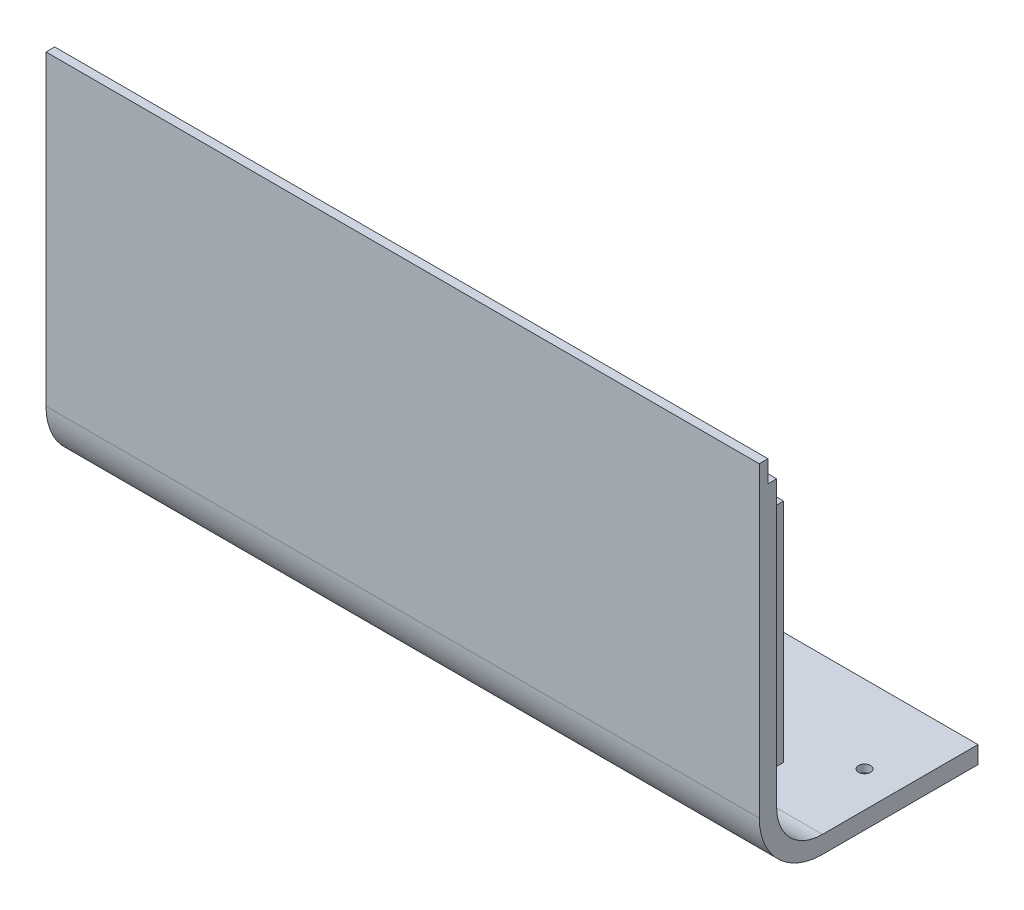
SolidWorks part; units mm, degrees
ref_plane "Alzado" through (0, 0, 0) normal (0, 0, 1) x (1, 0, 0)
ref_plane "Planta" through (0, 0, 0) normal (0, 1, 0) x (1, 0, 0)
ref_plane "Vista lateral" through (0, 0, 0) normal (1, 0, 0) x (0, 0, -1)
sketch "Croquis2" plane through (0, 0, 0) normal (1, 0, 0) x (0, 0, -1)
  line L0 (37, 0) -> (37, -3.2)
  line L1 (8.4, 0) -> (37, 0)
  line L2 (0, 8.4) -> (0, 239.6)
  line L3 (8.4, 248) -> (37, 248)
  line L5 (37, 248) -> (37, 251.2)
  line L6 (37, -3.2) -> (8.4, -3.2)
  line L7 (37, 251.2) -> (8.4, 251.2)
  line L8 (-3.2, 239.6) -> (-3.2, 8.4)
  arc A0 (8.4, 248) -> (0, 239.6) centre (8.4, 239.6) ccw
  arc A1 (0, 8.4) -> (8.4, 0) centre (8.4, 8.4) ccw
  arc A4 (8.4, 251.2) -> (-3.2, 239.6) centre (8.4, 239.6) ccw
  arc A5 (-3.2, 8.4) -> (8.4, -3.2) centre (8.4, 8.4) ccw
  point P9 (0, 0)
  dimension "D3" = 8.4
  dimension "D6" = 3.2
  dimension "D5" = 11.6
  dimension "D1" = 248
  dimension "D2" = 37
  dimension "D4" = 3.2
extrude "Saliente-Extruir1" add sketch "Croquis2" along normal blind 131.1
sketch "Croquis3" plane through (0, 251.2, 0) normal (0, 1, 0) x (1, 0, 0)
  line L0 (131.1, 37) -> (0, 37) construction
  line L1 (0, 37) -> (0, 8.4) construction
  line L2 (65.55, 37) -> (65.55, 8.4) construction
  line L4 (131.1, 8.4) -> (0, 8.4) construction
  circle A0 centre (6.55, 22.7) radius 1.1
  circle A1 centre (124.55, 22.7) radius 1.1
  dimension "D3" = 2.2
  dimension "D1" = 14.3
  dimension "D2" = 6.55
extrude "Cortar-Extruir1" cut sketch "Croquis3" against normal through all
sketch "Croquis4" plane through (0, 0, 3.2) normal (0, 0, 1) x (1, 0, 0)
  line L0 (131.1, 8.4) -> (0, 8.4) construction
  line L1 (0, 249.9) -> (0, 248) construction
  line L2 (65.55, 239.6) -> (65.55, 8.4) construction
  line L4 (5, 234) -> (126.1, 234)
  line L5 (126.1, 234) -> (126.1, 158.2)
  line L6 (126.1, 158.2) -> (5, 158.2)
  line L7 (5, 158.2) -> (5, 234)
  line L8 (0, 239.6) -> (0, 8.4) construction
  line L9 (131.1, 239.6) -> (0, 239.6) construction
  line L10 (8.4, 117) -> (8.4, 107)
  line L11 (40.7, 86.1) -> (50.7, 86.1)
  line L12 (40.7, 86.1) -> (40.7, 96.7)
  line L13 (40.7, 96.7) -> (50.7, 96.7)
  line L14 (50.7, 86.1) -> (50.7, 96.7)
  line L15 (5, 117) -> (6.6, 117)
  line L16 (5, 117) -> (5, 107)
  line L17 (5, 107) -> (6.6, 107)
  line L18 (6.6, 117) -> (6.6, 107)
  line L19 (8.4, 117) -> (10, 117)
  line L20 (10, 117) -> (10, 107)
  line L21 (8.4, 107) -> (10, 107)
  line L22 (11.8, 117) -> (11.8, 107)
  line L23 (11.8, 117) -> (13.4, 117)
  line L24 (13.4, 117) -> (13.4, 107)
  line L25 (11.8, 107) -> (13.4, 107)
  line L26 (15.2, 117) -> (15.2, 107)
  line L27 (15.2, 117) -> (16.8, 117)
  line L28 (16.8, 117) -> (16.8, 107)
  line L29 (15.2, 107) -> (16.8, 107)
  line L30 (18.6, 117) -> (18.6, 107)
  line L31 (18.6, 117) -> (20.2, 117)
  line L32 (20.2, 117) -> (20.2, 107)
  line L33 (18.6, 107) -> (20.2, 107)
  line L34 (22, 117) -> (22, 107)
  line L35 (22, 117) -> (23.6, 117)
  line L36 (23.6, 117) -> (23.6, 107)
  line L37 (22, 107) -> (23.6, 107)
  line L38 (25.4, 117) -> (25.4, 107)
  line L39 (25.4, 117) -> (27, 117)
  line L40 (27, 117) -> (27, 107)
  line L41 (25.4, 107) -> (27, 107)
  line L42 (28.8, 117) -> (28.8, 107)
  line L43 (28.8, 117) -> (30.4, 117)
  line L44 (30.4, 117) -> (30.4, 107)
  line L45 (28.8, 107) -> (30.4, 107)
  line L46 (32.2, 117) -> (32.2, 107)
  line L47 (32.2, 117) -> (33.8, 117)
  line L48 (33.8, 117) -> (33.8, 107)
  line L49 (32.2, 107) -> (33.8, 107)
  line L50 (35.6, 117) -> (35.6, 107)
  line L51 (35.6, 117) -> (37.2, 117)
  line L52 (37.2, 117) -> (37.2, 107)
  line L53 (35.6, 107) -> (37.2, 107)
  line L54 (39, 117) -> (39, 107)
  line L55 (39, 117) -> (40.6, 117)
  line L56 (40.6, 117) -> (40.6, 107)
  line L57 (39, 107) -> (40.6, 107)
  line L58 (42.4, 117) -> (42.4, 107)
  line L59 (42.4, 117) -> (44, 117)
  line L60 (44, 117) -> (44, 107)
  line L61 (42.4, 107) -> (44, 107)
  line L62 (45.8, 117) -> (45.8, 107)
  line L63 (45.8, 117) -> (47.4, 117)
  line L64 (47.4, 117) -> (47.4, 107)
  line L65 (45.8, 107) -> (47.4, 107)
  line L66 (49.2, 117) -> (49.2, 107)
  line L67 (49.2, 117) -> (50.8, 117)
  line L68 (50.8, 117) -> (50.8, 107)
  line L69 (49.2, 107) -> (50.8, 107)
  circle A0 centre (17, 79.6) radius 10.7
  circle A1 centre (65.55, 113.5) radius 5.07
  point P0 (5, 234)
  point P9 (126.1, 234)
  dimension "D6" = 21.4
  dimension "D16" = 10.14
  dimension "D2" = 121.1
  dimension "D3" = 75.8
  dimension "D4" = 17
  dimension "D5" = 168.4
  dimension "D7" = 23.7
  dimension "D8" = 151.3
  dimension "D9" = 10
  dimension "D10" = 10.6
  dimension "D11" = 131
  dimension "D12" = 10
  dimension "D13" = 1.6
  dimension "D14" = 5
  dimension "D17" = 134.5
  dimension "D18" = 14
  dimension "D15" = 14
extrude "Cortar-Extruir2" cut sketch "Croquis4" against normal through all
sketch "Croquis7" plane through (0, 0, 0) normal (0, 0, -1) x (-1, 0, 0)
  line L5 (-127.46, 125.3) -> (-127.96, 125.3)
  line L10 (-126.1, 234) -> (-127.46, 234)
  line L11 (-126.1, 234) -> (-126.1, 136)
  line L12 (-126.1, 136) -> (-127.46, 136)
  line L13 (-127.46, 234) -> (-127.46, 136)
  line L14 (-5, 234) -> (-3.64, 234)
  line L15 (-5, 234) -> (-5, 136)
  line L16 (-5, 136) -> (-3.64, 136)
  line L17 (-3.64, 234) -> (-3.64, 136)
  line L18 (-127.46, 125.3) -> (-126.1, 125.3)
  line L20 (-127.46, 66.3) -> (-126.1, 66.3)
  line L21 (-126.1, 125.3) -> (-126.1, 66.3)
  line L22 (-3.64, 125.3) -> (-5, 125.3)
  line L24 (-3.64, 66.3) -> (-5, 66.3)
  line L25 (-5, 125.3) -> (-5, 66.3)
  line L27 (-127.46, 66.3) -> (-127.96, 66.3)
  line L28 (-127.96, 125.3) -> (-127.96, 66.3)
  line L29 (-3.64, 125.3) -> (-3.14, 125.3)
  line L31 (-3.64, 66.3) -> (-3.14, 66.3)
  line L32 (-3.14, 125.3) -> (-3.14, 66.3)
  line L33 (-126.1, 53.5) -> (-127.96, 53.5)
  line L34 (-126.1, 53.5) -> (-126.1, 11.9)
  line L35 (-126.1, 11.9) -> (-127.96, 11.9)
  line L36 (-127.96, 53.5) -> (-127.96, 11.9)
  line L37 (-5, 53.5) -> (-3.14, 53.5)
  line L38 (-5, 53.5) -> (-5, 11.9)
  line L39 (-5, 11.9) -> (-3.14, 11.9)
  line L40 (-3.14, 53.5) -> (-3.14, 11.9)
  dimension "D1" = 1.36
  dimension "D2" = 98
  dimension "D3" = 10.7
  dimension "D4" = 59
  dimension "D5" = 0.5
  dimension "D6" = 0.5
  dimension "D7" = 12.8
  dimension "D8" = 1.36
  dimension "D9" = 1.36
  dimension "D10" = 0.5
  dimension "D11" = 1.36
  dimension "D12" = 41.6
extrude "Saliente-Extruir2" add sketch "Croquis7" along normal blind 4.4
sketch "Croquis8" plane through (0, 251.2, 0) normal (0, 1, 0) x (1, 0, 0)
  circle A0 centre (6.55, 22.7) radius 2.27
  circle A1 centre (124.55, 22.7) radius 2.27
  dimension "D1" = 4.54
extrude "Cortar-Extruir3" cut sketch "Croquis8" against normal blind 1.8
sketch "Croquis9" plane through (0, -3.2, 0) normal (0, -1, 0) x (1, 0, 0)
  circle A0 centre (124.55, -22.7) radius 2.27
  circle A1 centre (6.55, -22.7) radius 2.27
  dimension "D1" = 4.54
extrude "Cortar-Extruir4" cut sketch "Croquis9" against normal blind 1.8
sketch "Croquis10" plane through (0, 0, 0) normal (0, 0, -1) x (-1, 0, 0)
  line L0 (-40.7, 86.1) -> (-50.7, 86.1) construction
  line L1 (-50.7, 96.7) -> (-40.7, 96.7)
  line L2 (-50.7, 96.7) -> (-50.7, 86.1)
  line L3 (-50.7, 86.1) -> (-40.7, 86.1)
  line L4 (-40.7, 96.7) -> (-40.7, 86.1)
  line L5 (-51.9, 97.9) -> (-39.5, 97.9)
  line L6 (-39.5, 97.9) -> (-39.5, 84.9)
  line L7 (-39.5, 84.9) -> (-51.9, 84.9)
  line L8 (-51.9, 84.9) -> (-51.9, 97.9)
  line L9 (-40.7, 96.7) -> (-40.7, 86.1) construction
  circle A0 centre (-17, 79.6) radius 11.9
  circle A1 centre (-17, 79.6) radius 10.7 construction
  circle A2 centre (-17, 79.6) radius 10.7
  dimension "D1" = 1.2
  dimension "D2" = 1.2
  dimension "D3" = 1.2
  dimension "D4" = 1.2
  dimension "D5" = 1.2
extrude "Saliente-Extruir4" add sketch "Croquis10" along normal blind 8.6
fillet "Redondeo2" radius 1.28 4 edges at (50.7, 86.1, -2.7) (50.7, 96.7, -2.7) (40.7, 96.7, -2.7) (40.7, 86.1, -2.7)
ref_plane "Plano1" through (-10, 0, 0) normal (-1, 0, 0) x (0, 0, 1)
sketch "Croquis11" plane through (-10, 0, 0) normal (-1, 0, 0) x (0, 0, 1)
  line L0 (-8.6, 79.6) -> (0, 79.6) construction
  line L1 (-8.6, 91.5) -> (-8.6, 67.7) construction
  line L4 (-6.3, 72.6) -> (-2.3, 72.6)
  line L5 (-6.3, 72.6) -> (-6.3, 86.6)
  line L6 (-6.3, 86.6) -> (-2.3, 86.6)
  line L7 (-2.3, 72.6) -> (-2.3, 86.6)
  line L8 (-6.3, 72.6) -> (-2.3, 86.6) construction
  line L9 (-6.3, 86.6) -> (-2.3, 72.6) construction
  line L10 (0, 8.4) -> (0, 239.6) construction
  point P6 (-4.3, 79.6)
  dimension "D1" = 4
  dimension "D2" = 14
extrude "Cortar-Extruir5" cut sketch "Croquis11" against normal up to surface (18.9074 mm away)
sketch "Croquis13" plane through (0, 0, -8.6) normal (0, 0, -1) x (-1, 0, 0)
  line L0 (-49.42, 96.7) -> (-41.98, 96.7)
  line L1 (-49.42, 86.1) -> (-41.98, 86.1)
  line L2 (-40.7, 87.38) -> (-40.7, 95.42)
  line L3 (-50.7, 87.38) -> (-50.7, 95.42)
  line L4 (-51.9, 97.9) -> (-51.9, 84.9)
  line L5 (-51.9, 84.9) -> (-39.5, 84.9)
  line L6 (-39.5, 84.9) -> (-39.5, 97.9)
  line L7 (-39.5, 97.9) -> (-51.9, 97.9)
  line L8 (-51.9, 97.9) -> (-51.9, 84.9)
  line L9 (-51.9, 84.9) -> (-39.5, 84.9)
  line L10 (-39.5, 84.9) -> (-39.5, 97.9)
  line L11 (-39.5, 97.9) -> (-51.9, 97.9)
  circle A0 centre (-49.42, 95.42) radius 1.28
  circle A1 centre (-49.42, 87.38) radius 1.28
  circle A2 centre (-41.98, 87.38) radius 1.28
  circle A3 centre (-41.98, 95.42) radius 1.28
  line M5 (-51.9, 97.9) -> (-51.9, 84.9)
  line M6 (-51.9, 84.9) -> (-39.5, 84.9)
  line M7 (-39.5, 84.9) -> (-39.5, 97.9)
  line M8 (-39.5, 97.9) -> (-51.9, 97.9)
  line M9 (-50.7, 87.38) -> (-50.7, 95.42)
  arc M10 (-50.7, 95.42) -> (-49.42, 96.7) centre (-49.42, 95.42) cw
  line M11 (-49.42, 96.7) -> (-41.98, 96.7)
  arc M12 (-41.98, 96.7) -> (-40.7, 95.42) centre (-41.98, 95.42) cw
  line M13 (-40.7, 95.42) -> (-40.7, 87.38)
  arc M14 (-40.7, 87.38) -> (-41.98, 86.1) centre (-41.98, 87.38) cw
  line M15 (-41.98, 86.1) -> (-49.42, 86.1)
  arc M16 (-49.42, 86.1) -> (-50.7, 87.38) centre (-49.42, 87.38) cw
  dimension "D1" = 0
extrude "Saliente-Extruir6" add sketch "Croquis13" along normal blind 1 contours M8 M5 M6 M7 M16 M9 M10 M11 M12 M13 M14 M15
sketch "Croquis14" plane through (0, 0, 0) normal (0, 0, -1) x (-1, 0, 0)
  line L0 (-65.55, 113.5) -> (-65.55, 74.9205) construction
  circle A0 centre (-65.55, 88.8) radius 1.5
  circle A1 centre (-65.55, 88.8) radius 2.8
  dimension "D2" = 3
  dimension "D3" = 5.6
  dimension "D1" = 24.7
extrude "Saliente-Extruir7" add sketch "Croquis14" along normal blind 8.4
fillet "Redondeo3" radius 1.28 1 edges at (68.35, 88.8, 0)
sketch "Croquis17" plane through (127.46, 0, 0) normal (1, 0, 0) x (0, 0, -1)
  line L0 (4.4, 234) -> (4.4, 136) construction
  line L1 (0, 234) -> (4.4, 234)
  line L2 (0, 234) -> (0, 233.6)
  line L3 (0, 233.6) -> (4.4, 233.6)
  line L4 (4.4, 234) -> (4.4, 233.6)
  dimension "D1" = 0.4
extrude "Cortar-Extruir6" cut sketch "Croquis17" against normal through all
fillet "Redondeo4" radius 1.6 2 edges at (51.9, 91.4, 0) (39.5, 91.4, 0)
sketch "Croquis19" plane through (0, 0, 0) normal (0, 0, -1) x (-1, 0, 0)
  line L5 (-17, 67.7) -> (-17, 79.6) construction
  line L18 (-17, 79.6) -> (-17, 91.5) construction
  circle A2 centre (-17, 79.6) radius 11.9 construction
  circle A3 centre (-17, 91.5) radius 1.12
  circle A4 centre (-17, 67.7) radius 1.12
  dimension "D1" = 2.24
extrude "Saliente-Extruir8" add sketch "Croquis19" along normal up to surface (8.6 mm away) up to face at (5.1, 79.6, -8.6)
fillet "Redondeo5" radius 1 1 edges at (28.9, 79.6, 0)
sketch "Croquis21" plane through (127.96, 0, 0) normal (1, 0, 0) x (0, 0, -1)
  line L1 (4.4, 66.3) -> (3.8, 66.3)
  line L2 (4.4, 66.3) -> (4.4, 92.3)
  line L3 (4.4, 92.3) -> (3.8, 92.3)
  line L4 (3.8, 66.3) -> (3.8, 92.3)
  dimension "D1" = 0.6
  dimension "D2" = 26
extrude "Cortar-Extruir8" cut sketch "Croquis21" against normal up to vertex
sketch "Croquis23" plane through (0, 0, 3.2) normal (0, 0, 1) x (1, 0, 0)
  line L0 (126.1, 158.2) -> (126.1, 234) construction
  line L1 (5, 158.2) -> (126.1, 158.2)
  line L2 (5, 158.2) -> (5, 158.1)
  line L3 (5, 158.1) -> (126.1, 158.1)
  line L4 (126.1, 158.2) -> (126.1, 158.1)
  dimension "D1" = 0.1
extrude "Cortar-Extruir9" cut sketch "Croquis23" against normal through all
sketch "Croquis24" plane through (131.1, 0, 0) normal (1, 0, 0) x (0, 0, -1)
  line L0 (-3.2, 239.6) -> (-3.2, 8.4) construction
  line L1 (37, 251.2) -> (-3.2, 251.2)
  line L2 (37, 251.2) -> (37, 60.8)
  line L3 (37, 60.8) -> (-1.6, 60.8)
  line L4 (-3.2, 251.2) -> (-3.2, 64.8)
  line L5 (8.4, -3.2) -> (37, -3.2) construction
  line L6 (0, 58.1813) -> (-3.2, 58.1813) construction
  line L7 (0, 8.4) -> (0, 239.6) construction
  line L8 (-1.6, 60.8) -> (-1.6, 64.8)
  line L9 (-1.6, 64.8) -> (-3.2, 64.8)
  line L10 (-1.6, 64.8) -> (-3.2, 64.8)
  line L11 (-3.2, 64.8) -> (-3.2, -3.2)
  line L12 (37, -3.2) -> (-3.2, -3.2)
  line L13 (37, -3.2) -> (37, 60.8)
  line M8 (37, 248) -> (37, 251.2)
  line M9 (37, 251.2) -> (8.4, 251.2)
  arc M10 (8.4, 251.2) -> (-3.2, 239.6) centre (8.4, 239.6) ccw
  line M11 (-3.2, 239.6) -> (-3.2, 8.4)
  line M17 (0, 8.4) -> (0, 239.6)
  arc M18 (0, 239.6) -> (8.4, 248) centre (8.4, 239.6) cw
  line M19 (8.4, 248) -> (37, 248)
  dimension "D1" = 64
  dimension "D2" = 4
  dimension "D3" = 1.6
extrude "Cortar-Extruir10" cut sketch "Croquis24" against normal through all contours L3 L2 M19 M18 M17 | L9 L8 L3 M17 M18 M19 M8 M9 M10 M11
